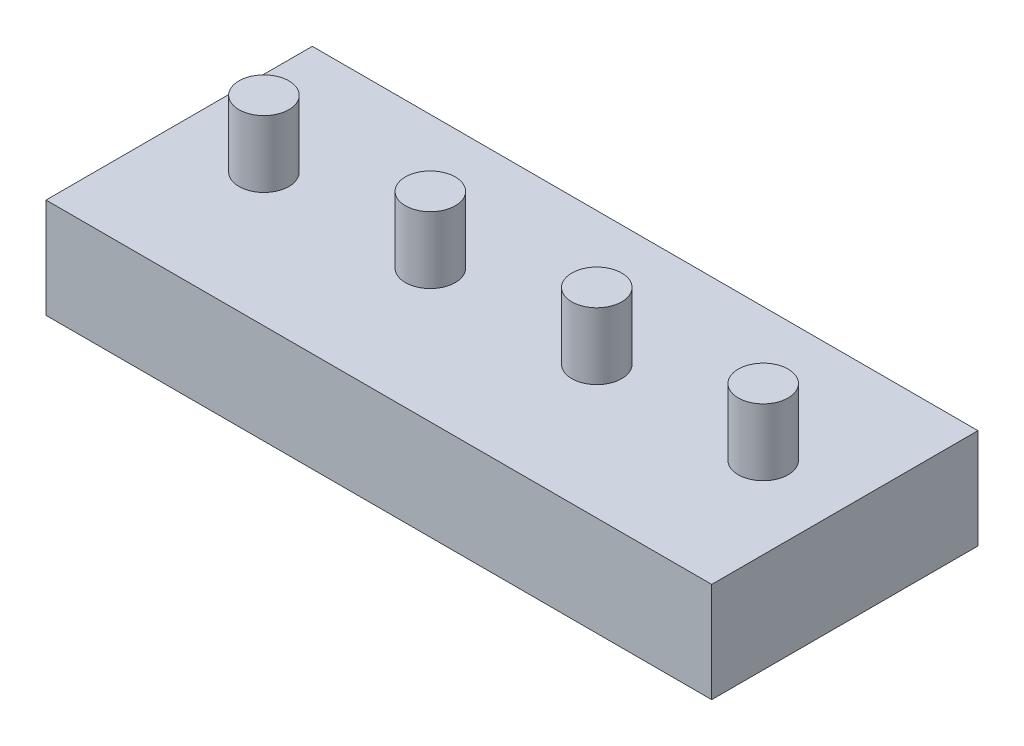
SolidWorks part; units mm, degrees
ref_plane "Front Plane" through (0, 0, 0) normal (0, 0, 1) x (1, 0, 0)
ref_plane "Top Plane" through (0, 0, 0) normal (0, 1, 0) x (1, 0, 0)
ref_plane "Right Plane" through (0, 0, 0) normal (1, 0, 0) x (0, 0, -1)
sketch "Sketch1" plane through (0, 0, 0) normal (0, 1, 0) x (1, 0, 0)
  line L1 (-10.0467, 4) -> (9.9533, 4)
  line L2 (-10.0467, 4) -> (-10.0467, -4)
  line L3 (-10.0467, -4) -> (9.9533, -4)
  line L4 (9.9533, 4) -> (9.9533, -4)
  dimension "D3" = 8
  dimension "D2" = 20
extrude "Boss-Extrude1" add sketch "Sketch1" along normal blind 3
sketch "Sketch2" plane through (0, 0, 0) normal (0, 1, 0) x (1, 0, 0)
  circle A0 centre (-7.5, 0) radius 0.75
  circle A1 centre (-2.5, 0) radius 0.75
  circle A2 centre (2.5, 0) radius 0.75
  circle A3 centre (7.5, 0) radius 0.75
  dimension "D1" = 1.5
extrude "Boss-Extrude2" add sketch "Sketch2" along normal blind 5 separate body
